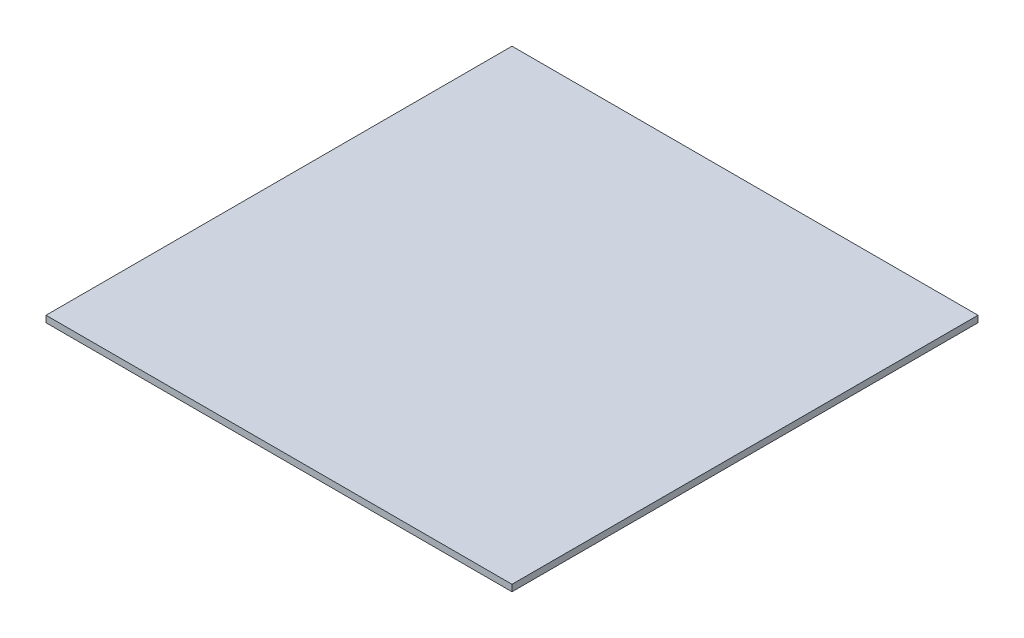
SolidWorks part; units mm, degrees
ref_plane "Спереди" through (0, 0, 0) normal (0, 0, 1) x (1, 0, 0)
ref_plane "Сверху" through (0, 0, 0) normal (0, 1, 0) x (1, 0, 0)
ref_plane "Справа" through (0, 0, 0) normal (1, 0, 0) x (0, 0, -1)
sketch "Эскиз1" plane through (0, 0, 0) normal (0, 1, 0) x (1, 0, 0)
  line L1 (0, 0) -> (214, 0)
  line L2 (0, 0) -> (0, 214)
  line L3 (0, 214) -> (214, 214)
  line L4 (214, 0) -> (214, 214)
  dimension "D1" = 214
  dimension "D2" = 214
extrude "Бобышка-Вытянуть1" add sketch "Эскиз1" along normal blind 3
